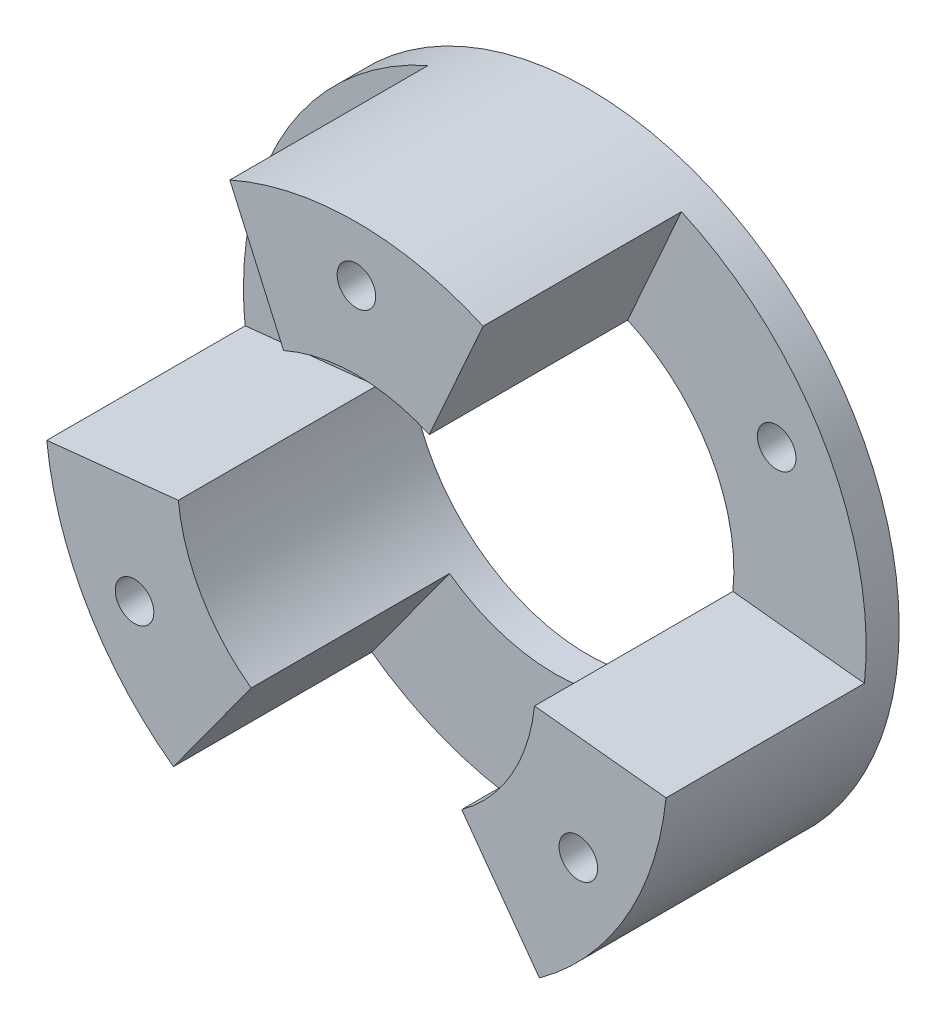
SolidWorks part; units mm, degrees
ref_plane "Front Plane" through (0, 0, 0) normal (0, 0, 1) x (1, 0, 0)
ref_plane "Top Plane" through (0, 0, 0) normal (0, 1, 0) x (1, 0, 0)
ref_plane "Right Plane" through (0, 0, 0) normal (1, 0, 0) x (0, 0, -1)
sketch "Sketch2" plane through (0, 0, 0) normal (1, 0, 0) x (0, 0, -1)
  line L0 (0, 0) -> (-36.2657, 0) construction
  line L1 (0, 0) -> (0, 28.25) construction
  line L2 (0, 28.25) -> (-3, 28.25)
  line L3 (-3, 28.25) -> (-3, 16.25)
  line L4 (-3, 16.25) -> (0, 16.25)
  line L5 (0, 16.25) -> (0, 28.25)
  dimension "D1" = 28.25
  dimension "D2" = 3
  dimension "D3" = 12
revolve "Revolve1" add sketch "Sketch2" angle 360 about L0
sketch "Sketch3" plane through (0, 0, 3) normal (0, 0, 1) x (1, 0, 0)
  line L0 (0, 0) -> (0, 28.25) construction
  line L1 (-6.6095, 14.8451) -> (-11.4903, 25.8077)
  line L2 (6.6095, 14.8451) -> (11.4903, 25.8077)
  circle A0 centre (0, 0) radius 28.25 construction
  circle A1 centre (0, 0) radius 16.25 construction
  arc A2 (6.6095, 14.8451) -> (-6.6095, 14.8451) centre (0, 0) ccw
  arc A3 (11.4903, 25.8077) -> (-11.4903, 25.8077) centre (0, 0) ccw
  dimension "D1" = 24
extrude "Boss-Extrude1" add sketch "Sketch3" along normal blind 18
pattern_circular "CirPattern1" count 3 over 360 about axis through (0, 0, 0) along (0, 0, 1) of "Boss-Extrude1"
sketch "Sketch4" plane through (0, 0, 21) normal (0, 0, 1) x (1, 0, 0)
  line L0 (0, 0) -> (0, 28.25) construction
  arc A0 (11.4903, 25.8077) -> (-11.4903, 25.8077) centre (0, 0) ccw construction
  circle A1 centre (0, 23.25) radius 1.75
  dimension "D2" = 3.5
  dimension "D1" = 23.25
extrude "Cut-Extrude1" cut sketch "Sketch4" against normal blind 12
pattern_circular "CirPattern2" count 3 over 360 about axis through (0, 0, 0) along (0, 0, 1) of "Cut-Extrude1"
sketch "Sketch5" plane through (0, 0, 3) normal (0, 0, 1) x (1, 0, 0)
  line L0 (0, 0) -> (0, -28.25) construction
  arc A0 (-16.6049, -22.8547) -> (16.6049, -22.8547) centre (0, 0) ccw construction
  circle A1 centre (0, -23.25) radius 1.75
  dimension "D2" = 3.5
  dimension "D1" = 23.25
extrude "Cut-Extrude2" cut sketch "Sketch5" against normal through all
pattern_circular "CirPattern3" count 3 over 360 about axis through (0, 0, 0) along (0, 0, 1) of "Cut-Extrude2"
equation "\"Module\"= 1.5mm"
equation "\"Number of teeth\"= 15"
equation "\"Internal Bearing 'r'\"= 4mm"
equation "\"External Bearing 'r'\"= 6mm"
equation "\"Bearing Depth\"= 6mm"
equation "\"Planet Path Radius\"= 10.5mm + ( ( \"Number of teeth\" + 2 ) * \"Module\" ) / 2"
equation "\"Pin Radius\"= 3mm"
equation "\"Fastening Holes\"= 3mm"
equation "\"D3@Sketch2\"=\"Pin Radius\" *4"
equation "\"D1@Sketch2\"=\"Planet Path Radius\" +5"
equation "\"Number of planets\"= 3"
equation "\"D1@Sketch3\"=(360 / \"Number of planets\" ) / 5"
equation "\"D1@Sketch4\"=\"Planet Path Radius\""
equation "\"D2@Sketch4\"=\"Fastening Holes\"+0.5"
equation "\"D1@CirPattern2\"=\"Number of planets\""
equation "\"D1@Sketch5\"=\"Planet Path Radius\""
equation "\"D2@Sketch5\"=\"Fastening Holes\" +0.5"
